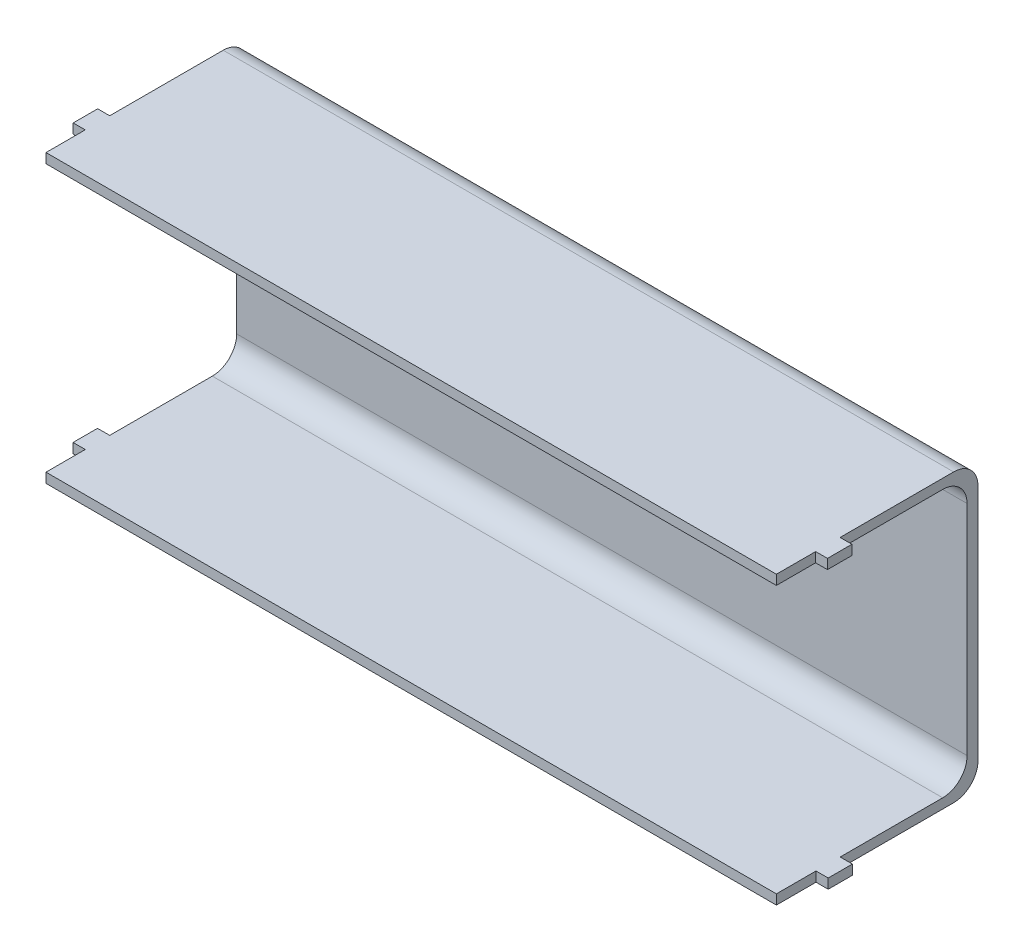
SolidWorks part; units mm, degrees
ref_plane "Front Plane" through (0, 0, 0) normal (0, 0, 1) x (1, 0, 0)
ref_plane "Top Plane" through (0, 0, 0) normal (0, 1, 0) x (1, 0, 0)
ref_plane "Right Plane" through (0, 0, 0) normal (1, 0, 0) x (0, 0, -1)
sketch "Sketch1" plane through (0, 0, 0) normal (1, 0, 0) x (0, 0, -1)
  line L0 (0, 42.1421) -> (36.9177, 42.1421)
  line L1 (41.9977, 37.0621) -> (41.9977, -12.4679)
  line L2 (36.9177, -17.5479) -> (0, -17.5479)
  line L3 (0, 42.1421) -> (0, 40.1167)
  line L4 (0, 40.1167) -> (34.6446, 40.1167)
  line L5 (39.7246, 35.0367) -> (39.7246, -10.4359)
  line L6 (34.6446, -15.5159) -> (0, -15.5159)
  line L7 (0, -15.5159) -> (0, -17.5479)
  arc A0 (36.9177, 42.1421) -> (41.9977, 37.0621) centre (36.9177, 37.0621) cw
  arc A1 (36.9177, -17.5479) -> (41.9977, -12.4679) centre (36.9177, -12.4679) ccw
  arc A2 (39.7246, -10.4359) -> (34.6446, -15.5159) centre (34.6446, -10.4359) cw
  arc A3 (34.6446, 40.1167) -> (39.7246, 35.0367) centre (34.6446, 35.0367) cw
  point P17 (0, 0)
  point P18 (0, 0)
  point P19 (0, 0)
  point P20 (40.2261, 34.5352)
  dimension "D1" = 5.08
  dimension "D2" = 5.08
  dimension "D6" = 5.08
  dimension "D7" = 5.08
  dimension "D3" = 59.69
  dimension "D4" = 2.0254
  dimension "D5" = 2.032
extrude "Boss-Extrude1" add sketch "Sketch1" against normal blind 152.146
sketch "Sketch2" plane through (0, 42.1421, 0) normal (0, 1, 0) x (1, 0, 0)
  line L0 (-152.146, 13.2692) -> (-154.6555, 13.2692)
  line L1 (-152.146, 36.9177) -> (-152.146, 0) construction
  line L2 (-154.6555, 13.2692) -> (-154.6555, 8.1772)
  line L3 (-154.6555, 8.1772) -> (-152.146, 8.1772)
  line L4 (-152.146, 8.1772) -> (-152.146, 13.2692)
  line L5 (0, 13.2692) -> (2.4574, 13.2692)
  line L6 (0, 36.9177) -> (0, 0) construction
  line L7 (2.4574, 13.2692) -> (2.4574, 8.1772)
  line L8 (2.4574, 8.1772) -> (0, 8.1772)
  line L9 (0, 8.1772) -> (0, 13.2692)
extrude "Boss-Extrude2" add sketch "Sketch2" against normal blind 2.032
sketch "Sketch3" plane through (0, 0, 0) normal (1, 0, 0) x (0, 0, -1)
  line L0 (34.6446, -15.5159) -> (0, -15.5159) construction
  line L1 (8.2527, -15.5159) -> (13.2907, -15.5159)
  line L2 (8.2527, -15.5159) -> (8.2527, -17.5479)
  line L3 (8.2527, -17.5479) -> (13.2907, -17.5479)
  line L4 (13.2907, -15.5159) -> (13.2907, -17.5479)
  line L5 (0, -17.5479) -> (36.9177, -17.5479) construction
  line L6 (8.1772, 40.1167) -> (8.2527, -15.5159) construction
  line L7 (13.2692, 40.1101) -> (13.2907, -15.5159) construction
sketch "Sketch4" plane through (-152.146, 0, 0) normal (-1, 0, 0) x (0, 0, 1)
  line L0 (-34.6446, -15.5159) -> (0, -15.5159) construction
  line L1 (-13.2692, -15.5159) -> (-8.1772, -15.5159)
  line L2 (-13.2692, -15.5159) -> (-13.2692, -17.5479)
  line L3 (-13.2692, -17.5479) -> (-8.1772, -17.5479)
  line L4 (-8.1772, -15.5159) -> (-8.1772, -17.5479)
  line L5 (0, -17.5479) -> (-36.9177, -17.5479) construction
  line L6 (-13.2692, 40.1167) -> (-13.2692, -15.5159) construction
  line L7 (-8.1772, 40.1167) -> (-8.1772, -15.5159) construction
extrude "Boss-Extrude3" add sketch "Sketch3" along normal blind 2.54
extrude "Boss-Extrude4" add sketch "Sketch4" along normal blind 2.54
